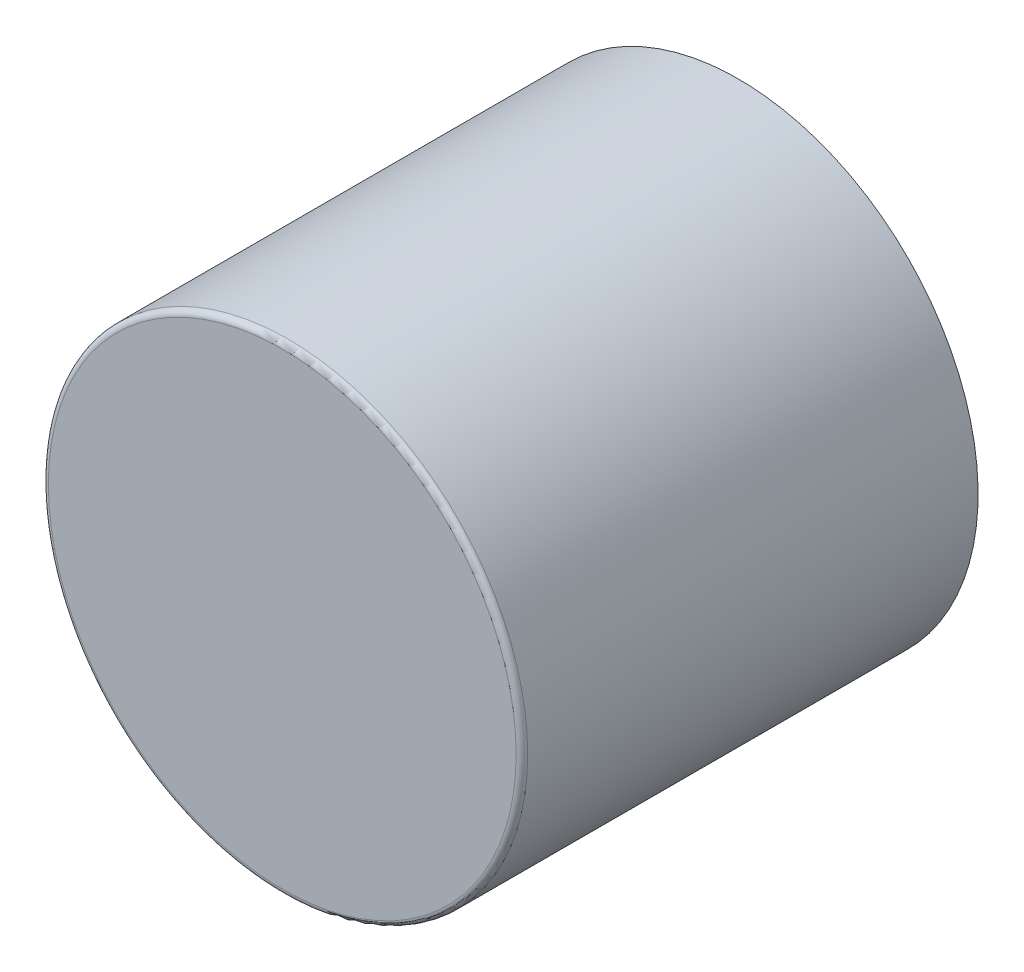
SolidWorks part; units mm, degrees
ref_plane "Plan de face" through (0, 0, 0) normal (0, 0, 1) x (1, 0, 0)
ref_plane "Plan de dessus" through (0, 0, 0) normal (0, 1, 0) x (1, 0, 0)
ref_plane "Plan de droite" through (0, 0, 0) normal (1, 0, 0) x (0, 0, -1)
sketch "Sketch6" plane through (0, 0, 0) normal (0, 0, -1) x (-1, 0, 0)
  point P0 (-11.097, 40.1323)
  point P1 (0, 0)
  point P3 (0, 0)
  point P4 (0, 0)
sketch "Esquisse1" plane through (0, 0, 0) normal (0, 0, 1) x (1, 0, 0)
  circle A0 centre (11.097, 40.1323) radius 41.5
  dimension "D3" = 83
extrude "Boss.-Extru.1" add sketch "Esquisse1" along normal blind 1.5
sketch "Esquisse2" plane through (0, 0, 0) normal (0, 0, -1) x (-1, 0, 0)
  circle A0 centre (-11.097, 40.1323) radius 40
  circle A1 centre (-11.097, 40.1323) radius 41.5
  circle A2 centre (-11.097, 40.1323) radius 41.5
  dimension "D2" = 1.5
  dimension "D1" = 0
extrude "Boss.-Extru.2" add sketch "Esquisse2" along normal blind 77.5
sketch "Esquisse4" plane through (0, 0, -77.5) normal (0, 0, -1) x (-1, 0, 0)
  line L2 (-19.7218, 1.0732) -> (-19.7218, -0.4616) construction
  line L4 (-21.0969, -0.1449) -> (-21.0969, 1.4024)
  line L5 (-1.0969, 1.4025) -> (-1.0969, -0.1449)
  line L9 (-51.097, 40.1323) -> (28.903, 40.1323) construction
  line L10 (-2.7218, -0.5138) -> (-2.7218, 1.0189) construction
  circle A0 centre (-11.097, 40.1323) radius 40 construction
  circle A1 centre (-11.097, 40.1323) radius 41.5 construction
  circle A3 centre (-11.097, 40.1323) radius 40 construction
  circle A9 centre (-11.097, 40.1323) radius 40 construction
  arc A11 (-19.7218, -0.4616) -> (-2.7218, -0.5138) centre (-11.097, 40.1323) ccw
  arc A12 (-19.7218, 1.0732) -> (-2.7218, 1.0189) centre (-11.097, 40.1323) ccw
  arc A15 (-21.0969, 1.4024) -> (-19.7218, 1.0732) centre (-11.097, 40.1323) ccw
  arc A16 (-21.0969, -0.1449) -> (-19.7218, -0.4616) centre (-11.097, 40.1323) ccw
  arc A17 (-2.7218, -0.5138) -> (-1.0969, -0.1449) centre (-11.097, 40.1323) ccw
  arc A18 (-2.7218, 1.0189) -> (-1.0969, 1.4025) centre (-11.097, 40.1323) ccw
  circle M6 centre (-11.097, 40.1323) radius 41.5
  circle M7 centre (-11.097, 40.1323) radius 40
  dimension "D2" = 20
  dimension "D1" = 17
extrude "Enlèv. mat.-Extru.2" cut sketch "Esquisse4" against normal blind 3 contours L5 L4 M7 M6
sketch "Esquisse5" plane through (0, 0, -74.5) normal (0, 0, -1) x (-1, 0, 0)
  line L0 (-19.597, 1.0459) -> (-19.597, -0.4879)
  line L1 (-2.597, 1.0459) -> (-2.597, -0.4879)
  line L2 (-1.0969, -0.1449) -> (-1.0969, 1.4025)
  line L3 (-21.0969, 1.4024) -> (-21.0969, -0.1449)
  line L4 (-1.0969, -0.1449) -> (-1.0969, 1.4025) construction
  line L5 (-21.0969, 1.4024) -> (-21.0969, -0.1449) construction
  line L6 (-19.597, 1.0459) -> (-2.597, 1.0459) construction
  arc A0 (-21.0969, -0.1449) -> (-19.597, -0.4879) centre (-11.097, 40.1323) ccw construction
  arc A1 (-21.0969, 1.4024) -> (-19.597, 1.0459) centre (-11.097, 40.1323) ccw construction
  arc A2 (-21.0969, 1.4024) -> (-1.0969, 1.4025) centre (-11.097, 40.1323) ccw
  arc A3 (-21.0969, -0.1449) -> (-1.0969, -0.1449) centre (-11.097, 40.1323) ccw
  arc A4 (-19.597, 1.0459) -> (-2.597, 1.0459) centre (-11.097, 40.1323) ccw
  arc A5 (-19.597, -0.4879) -> (-2.597, -0.4879) centre (-11.097, 40.1323) ccw
  arc A6 (-2.597, 1.0459) -> (-1.0969, 1.4025) centre (-11.097, 40.1323) ccw construction
  arc A7 (-2.597, -0.4879) -> (-1.0969, -0.1449) centre (-11.097, 40.1323) ccw construction
  point P10 (-11.097, 1.0459)
  dimension "D2" = 17
  dimension "D1" = 0
extrude "Enlèv. mat.-Extru.3" cut sketch "Esquisse5" against normal blind 15
sketch "Esquisse6" plane through (0, 0, 1.5) normal (0, 0, 1) x (1, 0, 0)
  line L0 (-30.403, 40.1323) -> (52.597, 40.1323) construction
  line L6 (8.75, 61.425) -> (8.75, 59.9166)
  line L8 (15.75, 61.425) -> (15.75, 59.9166)
  circle A0 centre (11.097, 40.1323) radius 41.5 construction
  arc A3 (15.75, 61.425) -> (8.75, 61.425) centre (12.25, 27.5) ccw
  arc A20 (15.75, 59.9166) -> (8.75, 59.9166) centre (12.25, 27.5) ccw
  dimension "D1" = 7
extrude "Enlèv. mat.-Extru.4" [suppressed] cut sketch "Esquisse6" against normal blind 15
ref_plane "Plane1" [suppressed] through (0, 1.0459, 0) normal (0, 1, 0) x (1, 0, 0)
sketch "Sketch1" [suppressed] plane through (0, 1.0459, 0) normal (0, 1, 0) x (1, 0, 0)
  line L1 (19.945, 59.5) -> (2.945, 59.5) construction
  line L2 (2.945, 74.5) -> (1.1175, 74.5) construction
  line L3 (1.1175, 74.5) -> (1.1175, 77.5) construction
  line L4 (2.945, 59.5) -> (2.945, 74.5) construction
  line L5 (19.945, 59.5) -> (19.945, 74.5) construction
  line L6 (21.1168, 74.5) -> (21.1168, 77.5) construction
  line L7 (21.1168, 74.5) -> (19.945, 74.5) construction
  line L9 (19.945, 59.5) -> (2.945, 59.5)
  line L10 (2.945, 74.5) -> (1.1175, 74.5) construction
  line L11 (1.1175, 74.5) -> (1.1175, 77.5) construction
  line L12 (2.945, 59.5) -> (2.945, 69)
  line L13 (19.945, 59.5) -> (19.945, 69)
  line L14 (21.1168, 74.5) -> (21.1168, 77.5) construction
  line L15 (21.1168, 74.5) -> (19.945, 74.5) construction
  line L17 (1.1175, 77.5) -> (0.1175, 77.5) construction
  line L18 (22.1168, 77.5) -> (21.1168, 77.5) construction
  line L19 (22.1168, 69) -> (22.1168, 60)
  line L20 (20.1168, 58) -> (2.1175, 58)
  line L21 (0.1175, 69) -> (0.1175, 60)
  line L22 (22.1168, 69) -> (19.945, 69)
  line L23 (19.945, 69) -> (19.945, 74.5) construction
  line L24 (22.1168, 77.5) -> (22.1168, 69) construction
  line L25 (2.945, 69) -> (0.1175, 69)
  line L26 (19.945, 69) -> (2.945, 69) construction
  line L27 (2.945, 69) -> (2.945, 74.5) construction
  line L28 (0.1175, 77.5) -> (0.1175, 69) construction
  arc A0 (22.1168, 60) -> (20.1168, 58) centre (20.1168, 60) cw
  arc A1 (2.1175, 58) -> (0.1175, 60) centre (2.1175, 60) cw
  dimension "D4" = 2
  dimension "D1" = 1.5
  dimension "D2" = 1
  dimension "D3" = 1
  dimension "D5" = 5.5
extrude "Boss-Extrude1" [suppressed] add sketch "Sketch1" against normal blind 59
sketch "Sketch2" [suppressed] plane through (0, 0, -58) normal (0, 0, 1) x (1, 0, 0)
  circle A0 centre (12.1828, -66.06) radius 8.33 construction
  arc A1 (2.1175, -0.3059) -> (20.1168, -0.4516) centre (11.445, 40.1323) ccw construction
  point P6 (11.1092, -1.3663)
  dimension "D1" = 16.66
  dimension "D2" = 64.7025
ref_plane "Plane2" [suppressed] through (0, -66.06, 0) normal (0, 1, 0) x (1, 0, 0)
sketch "Sketch3" [suppressed] plane through (0, -57.9541, 0) normal (0, -1, 0) x (1, 0, 0)
  line L0 (22.1168, -60) -> (22.1168, -69) construction
  line L1 (19.945, -69) -> (19.945, -59.5) construction
  line L2 (2.945, -59.5) -> (2.945, -69) construction
  line L3 (0.1175, -69) -> (0.1175, -60) construction
  line L4 (22.1168, -60) -> (22.1168, -69)
  line L5 (19.945, -69) -> (19.945, -59.5)
  line L6 (2.945, -59.5) -> (2.945, -69)
  line L7 (0.1175, -69) -> (0.1175, -60)
  line L8 (0.1175, -69) -> (2.945, -69)
  line L9 (19.945, -69) -> (22.1168, -69)
  line L10 (22.1168, -60) -> (22.1168, -50)
  line L11 (22.1168, -50) -> (0.1175, -50)
  line L12 (0.1175, -50) -> (0.1175, -60)
  line L13 (2.945, -59.5) -> (2.945, -51.5)
  line L14 (2.945, -51.5) -> (19.945, -51.5)
  line L15 (19.945, -51.5) -> (19.945, -59.5)
  line L16 (19.945, -59.5) -> (2.945, -59.5) construction
  dimension "D1" = 8
  dimension "D2" = 1.5
sketch "Sketch4" [suppressed] plane through (0, -66.06, 0) normal (0, 1, 0) x (1, 0, 0)
  line L0 (2.945, 59.5) -> (2.945, 53)
  line L1 (2.945, 51.5) -> (19.945, 51.5) construction
  line L2 (12.25, 51.5) -> (4.445, 51.5)
  line L4 (12.25, 50) -> (1.6175, 50)
  line L5 (22.1168, 50) -> (0.1175, 50) construction
  line L6 (0.1175, 51.5) -> (0.1175, 60)
  line L7 (2.945, 59.5) -> (2.945, 69) construction
  line L8 (2.945, 59.5) -> (0.1175, 60)
  line L9 (12.25, 51.5) -> (12.25, 50)
  arc A0 (2.945, 53) -> (4.445, 51.5) centre (4.445, 53) ccw
  arc A1 (1.6175, 50) -> (0.1175, 51.5) centre (1.6175, 51.5) cw
  point P21 (0.1175, 50)
  dimension "D1" = 1.5
revolve "Revolve1" [suppressed] add sketch "Sketch4" angle 360 about L9
sketch "Sketch5" [suppressed] plane through (0, -57.9541, 0) normal (0, -1, 0) x (1, 0, 0)
  line L7 (2.945, -59.5) -> (19.945, -59.5)
  line L8 (19.945, -59.5) -> (19.945, -69)
  line L9 (19.945, -69) -> (22.1168, -69)
  line L10 (22.1168, -69) -> (22.1168, -60)
  line L14 (19.945, -59.5) -> (19.945, -69)
  line L15 (19.945, -69) -> (22.1168, -69)
  line L16 (22.1168, -69) -> (22.1168, -60)
  line L18 (19.945, -59.5) -> (19.945, -69)
  line L19 (20.1168, -58) -> (2.1175, -58)
  line L20 (0.1175, -60) -> (0.1175, -69)
  line L21 (0.1175, -69) -> (2.945, -69)
  line L22 (2.945, -69) -> (2.945, -59.5)
  line L23 (2.945, -59.5) -> (19.945, -59.5)
  line L25 (20.1168, -58) -> (2.1175, -58)
  line L26 (0.1175, -60) -> (0.1175, -69)
  line L27 (0.1175, -69) -> (2.945, -69)
  line L28 (2.945, -69) -> (2.945, -59.5)
  line L30 (2.945, -59.5) -> (19.945, -59.5)
  line L34 (2.945, -59.5) -> (19.945, -59.5)
  line L35 (20.1168, -58) -> (2.1175, -58)
  line L36 (20.1168, -58) -> (2.1175, -58)
  line L37 (0.1175, -60) -> (0.1175, -69)
  line L38 (0.1175, -60) -> (0.1175, -69)
  line L39 (0.1175, -69) -> (2.945, -69)
  line L40 (0.1175, -69) -> (2.945, -69)
  line L41 (2.945, -69) -> (2.945, -59.5)
  line L42 (2.945, -69) -> (2.945, -59.5)
  line L43 (19.945, -59.5) -> (19.945, -69)
  line L44 (19.945, -69) -> (22.1168, -69)
  line L45 (19.945, -69) -> (22.1168, -69)
  line L46 (22.1168, -69) -> (22.1168, -60)
  line L47 (22.1168, -69) -> (22.1168, -60)
  arc A1 (22.1168, -60) -> (20.1168, -58) centre (20.1168, -60) ccw
  arc A2 (22.1168, -60) -> (20.1168, -58) centre (20.1168, -60) ccw
  arc A3 (2.1175, -58) -> (0.1175, -60) centre (2.1175, -60) ccw
  arc A4 (2.1175, -58) -> (0.1175, -60) centre (2.1175, -60) ccw
  arc A6 (2.1175, -58) -> (0.1175, -60) centre (2.1175, -60) ccw
  arc A8 (2.1175, -58) -> (0.1175, -60) centre (2.1175, -60) ccw
  arc A9 (22.1168, -60) -> (20.1168, -58) centre (20.1168, -60) ccw
  arc A10 (22.1168, -60) -> (20.1168, -58) centre (20.1168, -60) ccw
  dimension "D1" = 0
  dimension "D2" = 0
extrude "Boss-Extrude2" [suppressed] add sketch "Sketch5" along normal up to surface (16.2092 mm away)
fillet "Fillet1" radius 1 2 edges at (52.597, 40.1323, 1.5) (-28.903, 40.1323, 0)
